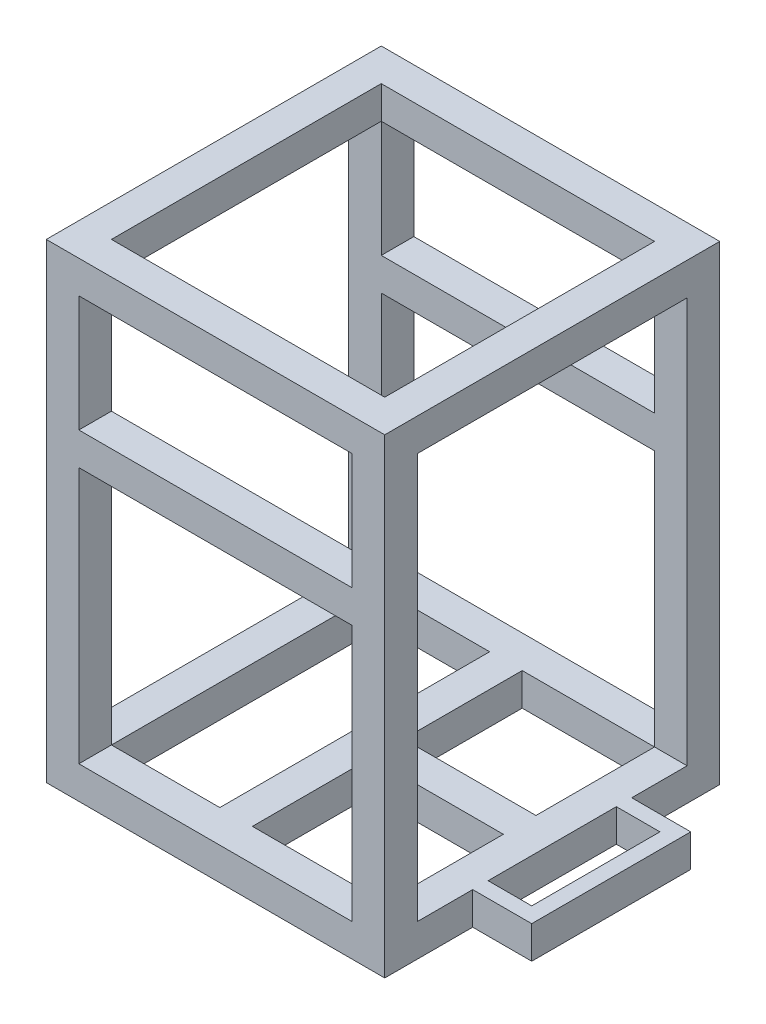
SolidWorks part; units mm, degrees
ref_plane "Front" through (0, 0, 0) normal (0, 0, 1) x (1, 0, 0)
ref_plane "Top" through (0, 0, 0) normal (0, 1, 0) x (1, 0, 0)
ref_plane "Right" through (0, 0, 0) normal (1, 0, 0) x (0, 0, -1)
sketch "Croquis1" plane through (0, 0, 0) normal (0, 1, 0) x (1, 0, 0)
  line L0 (131.9512, 65.3) -> (54.9512, 65.3) construction
  line L1 (0, 0) -> (131.9512, 0)
  line L2 (0, 0) -> (0, 130.6)
  line L3 (0, 130.6) -> (131.9512, 130.6)
  line L4 (131.9512, 0) -> (131.9512, 130.6)
  line L5 (12.7, 12.7) -> (54.9512, 12.7)
  line L6 (12.7, 12.7) -> (12.7, 117.9)
  line L7 (12.7, 117.9) -> (54.9512, 117.9)
  line L8 (119.2512, 12.7) -> (119.2512, 58.95)
  line L9 (54.9512, 65.3) -> (61.3012, 65.3) construction
  line L10 (54.9512, 12.7) -> (54.9512, 117.9)
  line L12 (67.6512, 117.9) -> (119.2512, 117.9)
  line L13 (67.6512, 12.7) -> (119.2512, 12.7)
  line L14 (119.2512, 71.65) -> (67.6512, 71.65)
  line L15 (119.2512, 58.95) -> (67.6512, 58.95)
  line L16 (119.2512, 71.65) -> (119.2512, 117.9)
  line L17 (67.6512, 12.7) -> (67.6512, 58.95)
  line L18 (67.6512, 71.65) -> (67.6512, 117.9)
  dimension "D1" = 105.2
  dimension "D2" = 12.7
  dimension "D3" = 12.7
  dimension "D4" = 12.7
  dimension "D5" = 12.7
  dimension "D6" = 77
  dimension "D7" = 6.35
  dimension "D10" = 6.35
  dimension "D9" = 12.7
extrude "Saliente-Extruir1" add sketch "Croquis1" along normal blind 12.7
sketch "Croquis2" plane through (0, 12.7, 0) normal (0, 1, 0) x (1, 0, 0)
  line L1 (12.7, 117.9) -> (0, 117.9)
  line L2 (12.7, 117.9) -> (12.7, 130.6)
  line L3 (12.7, 130.6) -> (0, 130.6)
  line L4 (0, 117.9) -> (0, 130.6)
  line L5 (12.7, 12.7) -> (0, 12.7)
  line L6 (12.7, 12.7) -> (12.7, 0)
  line L7 (12.7, 0) -> (0, 0)
  line L8 (0, 12.7) -> (0, 0)
  line L9 (119.2512, 117.9) -> (131.9512, 117.9)
  line L10 (119.2512, 117.9) -> (119.2512, 130.6)
  line L11 (119.2512, 130.6) -> (131.9512, 130.6)
  line L12 (131.9512, 117.9) -> (131.9512, 130.6)
  line L13 (119.2512, 12.7) -> (131.9512, 12.7)
  line L14 (119.2512, 12.7) -> (119.2512, 0)
  line L15 (119.2512, 0) -> (131.9512, 0)
  line L16 (131.9512, 12.7) -> (131.9512, 0)
extrude "Saliente-Extruir2" add sketch "Croquis2" along normal blind 158
sketch "Croquis3" plane through (0, 170.7, 0) normal (0, 1, 0) x (1, 0, 0)
  line L1 (0, 0) -> (131.9512, 0)
  line L2 (0, 0) -> (0, 130.6)
  line L3 (0, 130.6) -> (131.9512, 130.6)
  line L4 (131.9512, 0) -> (131.9512, 130.6)
  line L20 (12.7, 12.7) -> (119.2512, 12.7)
  line L21 (12.7, 12.7) -> (12.7, 117.9)
  line L22 (12.7, 117.9) -> (119.2512, 117.9)
  line L23 (119.2512, 12.7) -> (119.2512, 117.9)
extrude "Saliente-Extruir3" add sketch "Croquis3" along normal blind 12.7
sketch "Croquis4" plane through (119.2512, 0, 0) normal (-1, 0, 0) x (0, 0, 1)
  line L0 (0, 170.7) -> (0, 12.7) construction
  line L1 (0, 125.4) -> (-12.7, 125.4)
  line L2 (0, 125.4) -> (0, 112.7)
  line L3 (0, 112.7) -> (-12.7, 112.7)
  line L4 (-12.7, 125.4) -> (-12.7, 112.7)
  line L5 (-12.7, 170.7) -> (-12.7, 12.7) construction
  line L6 (-12.7, 12.7) -> (0, 12.7) construction
  line L7 (-65.3, 0) -> (-65.3, 170.7) construction
  line L8 (-130.6, 0) -> (0, 0) construction
  line L9 (-12.7, 170.7) -> (-117.9, 170.7) construction
  line L10 (-117.9, 125.4) -> (-117.9, 112.7)
  line L11 (-130.6, 112.7) -> (-117.9, 112.7)
  line L12 (-130.6, 125.4) -> (-130.6, 112.7)
  line L13 (-130.6, 125.4) -> (-117.9, 125.4)
  dimension "D1" = 100
  dimension "D2" = 12.7
extrude "Saliente-Extruir4" add sketch "Croquis4" along normal up to next
sketch "Croquis5" plane through (0, 12.7, 0) normal (0, 1, 0) x (1, 0, 0)
  line L1 (131.9512, 96.3) -> (154.9512, 96.3)
  line L3 (131.9512, 34.3) -> (154.9512, 34.3)
  line L4 (154.9512, 96.3) -> (154.9512, 34.3)
  line L5 (131.9512, 40.3) -> (148.9512, 40.3)
  line L6 (148.9512, 90.3) -> (148.9512, 40.3)
  line L7 (131.9512, 90.3) -> (148.9512, 90.3)
  line L9 (131.9512, 34.3) -> (131.9512, 40.3)
  line L10 (131.9512, 0) -> (131.9512, 130.6) construction
  line L11 (119.2512, 96.3) -> (154.9512, 96.3) construction
  line L12 (125.2512, 90.3) -> (148.9512, 90.3) construction
  line L13 (125.2512, 40.3) -> (148.9512, 40.3) construction
  line L14 (119.2512, 34.3) -> (154.9512, 34.3) construction
  line L15 (119.2512, 96.3) -> (119.2512, 34.3) construction
  line L16 (125.2512, 90.3) -> (125.2512, 40.3) construction
  line L17 (131.9512, 65.3) -> (154.9512, 65.3) construction
  line L18 (0, 0) -> (131.9512, 0) construction
  line L20 (131.9512, 90.3) -> (131.9512, 96.3)
  dimension "D2" = 23
  dimension "D3" = 25
  dimension "D4" = 65.3
  dimension "D1" = 6
extrude "Saliente-Extruir5" add sketch "Croquis5" against normal up to surface (12.7 mm away) up to face at (65.9756, 0, -65.3)
